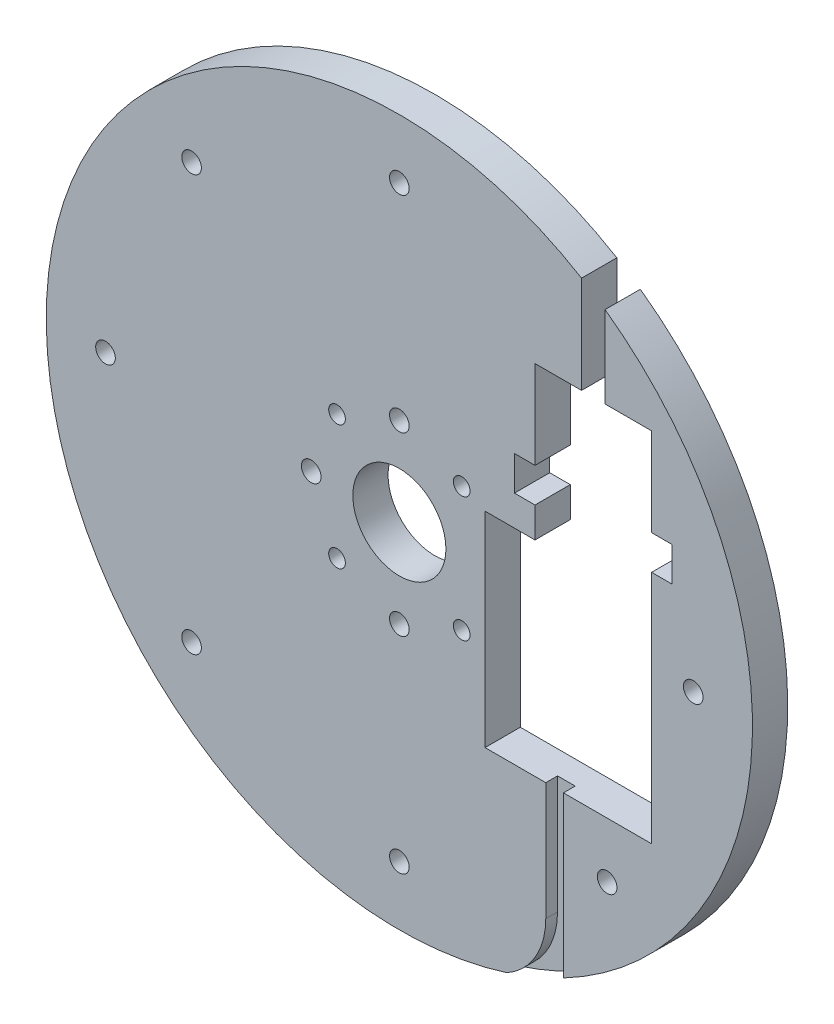
SolidWorks part; units mm, degrees
material "Balsa"
ref_plane "Front Plane" through (0, 0, 0) normal (0, 0, 1) x (1, 0, 0)
ref_plane "Top Plane" through (0, 0, 0) normal (0, 1, 0) x (1, 0, 0)
ref_plane "Right Plane" through (0, 0, 0) normal (1, 0, 0) x (0, 0, -1)
sketch "Sketch1" plane through (0, 0, 0) normal (0, 0, 1) x (1, 0, 0)
  circle A2 centre (0, 0) radius 60
  circle A3 centre (0, 0) radius 8
  circle A4 centre (0, 0) radius 15 construction
  circle A6 centre (0, 0) radius 50 construction
  circle A27 centre (0, -15) radius 1.75
  circle A28 centre (10.6066, -10.6066) radius 1.5
  circle A30 centre (0, -50) radius 1.75
  circle A31 centre (-15, 0) radius 1.75
  circle A32 centre (-10.6066, -10.6066) radius 1.5
  circle A33 centre (0, 15) radius 1.75
  circle A34 centre (-10.6066, 10.6066) radius 1.5
  circle A35 centre (15, 0) radius 1.75 construction
  circle A36 centre (10.6066, 10.6066) radius 1.5
  circle A38 centre (-35.3553, -35.3553) radius 1.75
  circle A40 centre (-50, 0) radius 1.75
  circle A42 centre (-35.3553, 35.3553) radius 1.75
  circle A44 centre (0, 50) radius 1.75
  circle A46 centre (35.3553, 35.3553) radius 1.75 construction
  circle A48 centre (50, 0) radius 1.75
  circle A50 centre (35.3553, -35.3553) radius 1.75
  dimension "D1" = 120
  dimension "D6" = 100
  dimension "D8" = 30
  dimension "D15" = 3.5
  dimension "D17" = 3.5
  dimension "D18" = 3
  dimension "D3" = 16
  dimension "D19" = 45
  dimension "D20" = 4
  dimension "D21" = 8
extrude "Boss-Extrude1" add sketch "Sketch1" along normal blind 6
sketch "Sketch2" plane through (0, 0, 6) normal (0, 0, 1) x (1, 0, 0)
  line L0 (14.5, -26) -> (43, -26)
  line L1 (43, -26) -> (43, 14)
  line L2 (43, 14) -> (46.5, 14)
  line L3 (46.5, 14) -> (46.5, 20)
  line L4 (46.5, 20) -> (43, 20)
  line L5 (43, 20) -> (43, 35)
  line L6 (43, 35) -> (23, 35)
  line L7 (23, 35) -> (23, 20)
  line L8 (23, 20) -> (19.5, 20)
  line L9 (19.5, 20) -> (19.5, 14)
  line L10 (19.5, 14) -> (23, 14)
  line L11 (23, 14) -> (23, 9)
  line L12 (23, 9) -> (14.5, 9)
  line L13 (14.5, 9) -> (14.5, -26)
  dimension "D1" = 20
  dimension "D2" = 3.5
  dimension "D3" = 3.5
  dimension "D4" = 15
  dimension "D5" = 6
  dimension "D6" = 5
  dimension "D7" = 40
  dimension "D8" = 8.5
  dimension "D9" = 35
  dimension "D10" = 23
extrude "Cut-Extrude1" cut sketch "Sketch2" against normal through all
other "Move Face1" face at (60, 0, 6) face at (23, 11.5, 3) face at (8, 0, 6) face at (1.75, -15, 6) face at (12.1066, -10.6066, 6) face at (1.75, -50, 6) face at (-13.25, 0, 6) face at (-9.1066, -10.6066, 6) face at (1.75, 15, 6) face at (-9.1066, 10.6066, 6) face at (12.1066, 10.6066, 6) face at (-33.6053, -35.3553, 6) face at (-48.25, 0, 6) face at (-33.6053, 35.3553, 6) face at (1.75, 50, 6) face at (51.75, 0, 6) face at (37.1053, -35.3553, 6) face at (23, 27.5, 3) face at (18.75, 9, 3) face at (21.25, 14, 3) face at (21.25, 20, 3) face at (33, 35, 3) face at (28.75, -26, 3) face at (43, -6, 3) face at (44.75, 14, 3) face at (46.5, 17, 3) face at (44.75, 20, 3) face at (43, 27.5, 3) face at (19.5, 17, 3) face at (14.5, -8.5, 3) parameters "D1"=0.08
sketch "Sketch3" plane through (0, 0, 6) normal (0, 0, 1) x (1, 0, 0)
  line L0 (24.9104, -45.959) -> (24.9104, -25.92)
  line L1 (24.9104, -25.92) -> (27.9104, -25.92)
  line L2 (27.9104, -25.92) -> (27.9104, -58.8694)
  line L3 (12, -58.8694) -> (27.9104, -58.8694)
  line L4 (0, 0) -> (0, -60.08) construction
  line L5 (14.58, -25.92) -> (42.92, -25.92) construction
  arc A0 (12, -58.8694) -> (24.9104, -45.959) centre (12, -45.959) ccw
  circle A1 centre (0, 0) radius 60.08 construction
  dimension "D1" = 12
  dimension "D2" = 3
  dimension "D3" = 45.959
extrude "Cut-Extrude2" cut sketch "Sketch3" against normal blind 2
sketch "Sketch4" plane through (0, 0, 6) normal (0, 0, 1) x (1, 0, 0)
  line L0 (42.92, 34.92) -> (23.08, 34.92) construction
  line L1 (31, 14.92) -> (35, 14.92)
  line L2 (31, 14.92) -> (31, 54.92)
  line L3 (31, 54.92) -> (35, 54.92)
  line L4 (35, 14.92) -> (35, 54.92)
  line L5 (31, 14.92) -> (35, 54.92) construction
  line L6 (31, 54.92) -> (35, 14.92) construction
  point P0 (33, 34.92)
  dimension "D1" = 40
  dimension "D2" = 4
extrude "Cut-Extrude3" cut sketch "Sketch4" against normal through all
